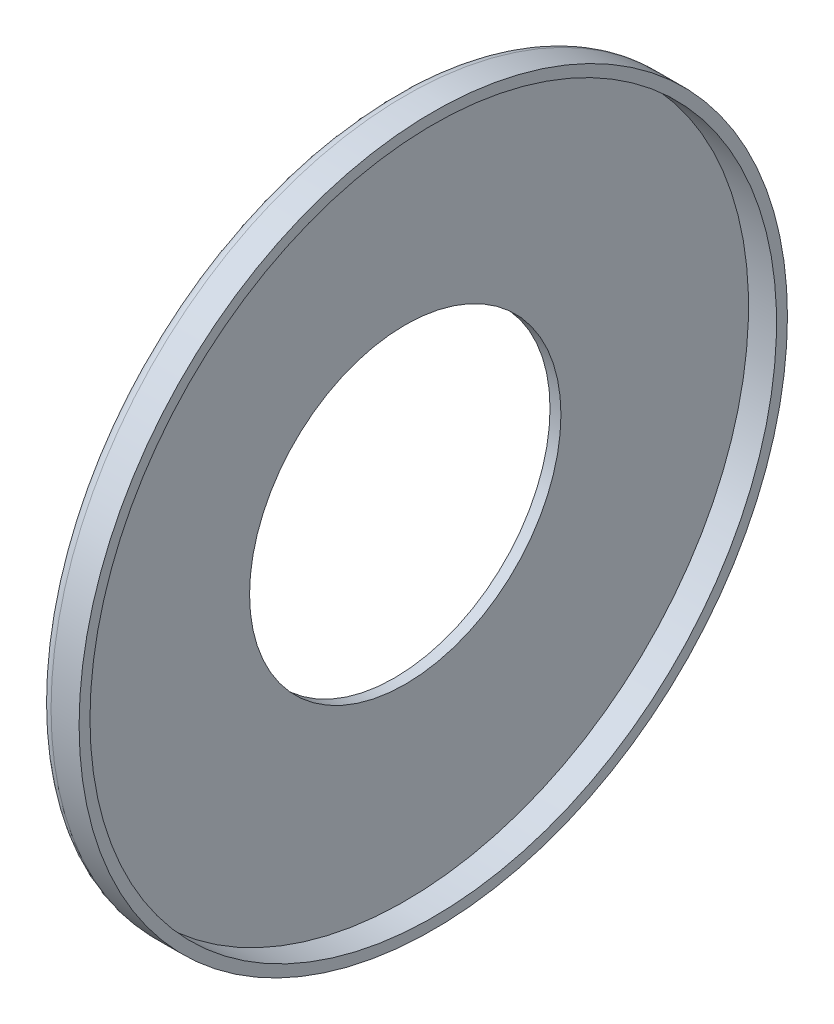
SolidWorks part; units mm, degrees
ref_plane "Alzado" through (0, 0, 0) normal (0, 0, 1) x (1, 0, 0)
ref_plane "Planta" through (0, 0, 0) normal (0, 1, 0) x (1, 0, 0)
ref_plane "Vista lateral" through (0, 0, 0) normal (1, 0, 0) x (0, 0, -1)
sketch "Croquis1" plane through (0, 0, 0) normal (0, 0, 1) x (1, 0, 0)
  line L0 (0.7, 10) -> (0.7, 22.05)
  line L1 (0.7, 22.05) -> (2.5, 22.05)
  line L2 (2.5, 22.05) -> (2.5, 22.75)
  line L3 (2.5, 22.75) -> (0.7, 22.75)
  line L8 (0, 10) -> (0.7, 10)
  line L9 (0, 10) -> (0, 22.05)
  line L10 (0, 10) -> (0, 17.0363) construction
  line L11 (0.7, 10) -> (0.7, 17.0363) construction
  line L13 (0, 0) -> (20.0871, 0) construction
  arc A0 (0.7, 22.75) -> (0, 22.05) centre (0.7, 22.05) ccw
  dimension "D5" = 0.7
  dimension "D3" = 2.5
  dimension "D4" = 10
  dimension "D8" = 0.7
  dimension "D1" = 45.5
  dimension "D2" = 0.7
revolve "Revolución1" add sketch "Croquis1" angle 360 about L13
